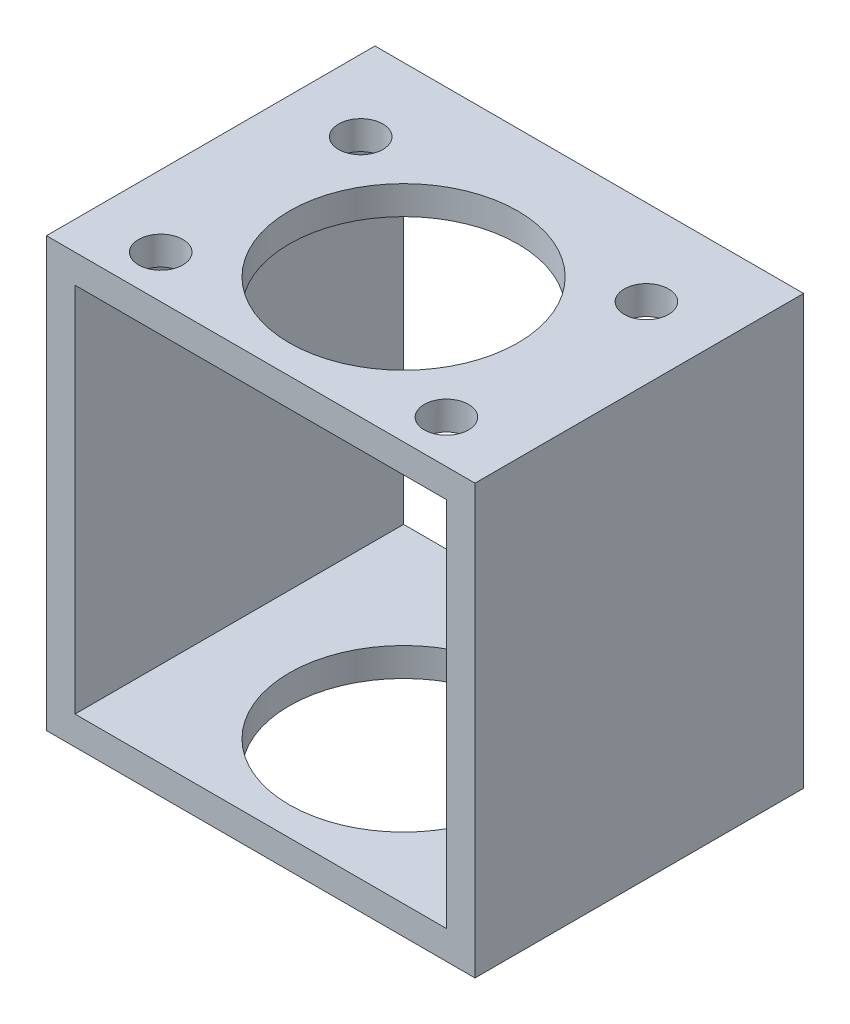
SolidWorks part; units mm, degrees
ref_plane "Front Plane" through (0, 0, 0) normal (0, 0, 1) x (1, 0, 0)
ref_plane "Top Plane" through (0, 0, 0) normal (0, 1, 0) x (1, 0, 0)
ref_plane "Right Plane" through (0, 0, 0) normal (1, 0, 0) x (0, 0, -1)
sketch "Sketch1" plane through (0, 0, 0) normal (0, 0, 1) x (1, 0, 0)
  line L1 (-15, -15) -> (15, -15)
  line L2 (-15, -15) -> (-15, 15)
  line L3 (-15, 15) -> (15, 15)
  line L4 (15, -15) -> (15, 15)
  line L5 (-15, -15) -> (15, 15) construction
  line L6 (-15, 15) -> (15, -15) construction
  line L7 (-13, 13) -> (13, 13)
  line L8 (-13, 13) -> (-13, -13)
  line L9 (-13, -13) -> (13, -13)
  line L10 (13, 13) -> (13, -13)
  line L11 (-13, 13) -> (13, -13) construction
  line L12 (-13, -13) -> (13, 13) construction
  point P0 (0, 0)
  point P5 (0, 0)
  dimension "D1" = 2
  dimension "D2" = 30
extrude "Boss-Extrude1" add sketch "Sketch1" along normal blind 23
sketch "Sketch2" plane through (0, -13, 0) normal (0, 1, 0) x (1, 0, 0)
  line L0 (0, 0) -> (0, -23) construction
  line L1 (15, -23) -> (-15, -23) construction
  line L2 (-15, -13) -> (15, -13) construction
  line L5 (-13, -23) -> (13, -23) construction
  circle A0 centre (0, -13) radius 8
  dimension "D1" = 16
  dimension "D2" = 10
extrude "Cut-Extrude1" cut sketch "Sketch2" along normal blind 30 and the other way blind 3
sketch "Sketch4" plane through (0, 15, 0) normal (0, 1, 0) x (1, 0, 0)
  line L0 (-15, -6) -> (15, -6) construction
  line L1 (-15, -23) -> (-15, 0) construction
  line L2 (15, -23) -> (15, 0) construction
  line L3 (-15, -20) -> (15, -20) construction
  line L4 (0, -23) -> (0, 0) construction
  line L5 (-10, -6) -> (-10, -20) construction
  line L6 (10, -6) -> (10, -20) construction
  line L8 (15, -23) -> (-15, -23) construction
  line L9 (-13, -23) -> (-13, 0) construction
  line L10 (13, -23) -> (13, 0) construction
  line L11 (-15, -13) -> (15, -13) construction
  line L12 (-15, -13) -> (15, -13) construction
  circle A0 centre (-10, -6) radius 1.55
  circle A1 centre (10, -6) radius 1.55
  circle A2 centre (10, -20) radius 1.55
  circle A3 centre (-10, -20) radius 1.55
  dimension "D1" = 3.1
  dimension "D2" = 7
  dimension "D3" = 3
  dimension "D4" = 3
  dimension "D5" = 3
  dimension "D6" = 7
extrude "Cut-Extrude2" cut sketch "Sketch4" against normal blind 3
